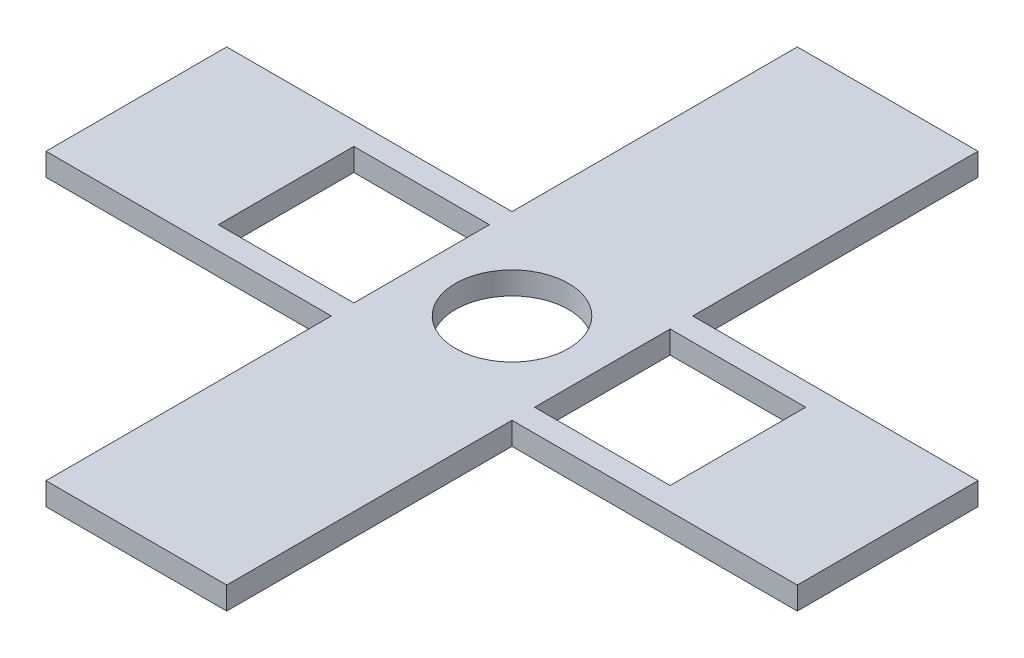
SolidWorks part; units mm, degrees
ref_plane "Front Plane" through (0, 0, 0) normal (0, 0, 1) x (1, 0, 0)
ref_plane "Top Plane" through (0, 0, 0) normal (0, 1, 0) x (1, 0, 0)
ref_plane "Right Plane" through (0, 0, 0) normal (1, 0, 0) x (0, 0, -1)
sketch "Sketch2" plane through (0, 0, 0) normal (0, 1, 0) x (1, 0, 0)
  line L0 (-21.1201, -5.08) -> (-5.08, -5.08)
  line L1 (-21.1201, 5.08) -> (-5.08, 5.08)
  line L2 (5.08, 3.81) -> (12.7, 3.81)
  line L3 (-12.7, 3.81) -> (-5.08, 3.81)
  line L4 (-12.7, 3.81) -> (-12.7, -3.81)
  line L5 (-12.7, -3.81) -> (-5.08, -3.81)
  line L6 (-5.08, 3.81) -> (-5.08, -3.81)
  line L7 (-12.7, 3.81) -> (-5.08, -3.81) construction
  line L8 (-12.7, -3.81) -> (-5.08, 3.81) construction
  line L9 (5.08, 3.81) -> (5.08, -3.81)
  line L10 (5.08, -3.81) -> (12.7, -3.81)
  line L11 (12.7, 3.81) -> (12.7, -3.81)
  line L12 (5.08, 3.81) -> (12.7, -3.81) construction
  line L13 (5.08, -3.81) -> (12.7, 3.81) construction
  line L14 (-21.1201, 5.08) -> (-21.1201, -5.08)
  line L15 (21.1201, -5.08) -> (5.08, -5.08)
  line L16 (21.1201, 5.08) -> (21.1201, -5.08)
  line L17 (-21.1201, 5.08) -> (21.1201, -5.08) construction
  line L18 (-21.1201, -5.08) -> (21.1201, 5.08) construction
  line L19 (-5.08, 21.1201) -> (5.08, 21.1201)
  line L20 (-5.08, 21.1201) -> (-5.08, 5.08)
  line L21 (-5.08, -21.1201) -> (5.08, -21.1201)
  line L22 (5.08, 21.1201) -> (5.08, 5.08)
  line L23 (-5.08, 21.1201) -> (5.08, -21.1201) construction
  line L24 (-5.08, -21.1201) -> (5.08, 21.1201) construction
  line L25 (5.08, 5.08) -> (21.1201, 5.08)
  line L26 (-5.08, -5.08) -> (-5.08, -21.1201)
  line L27 (5.08, -5.08) -> (5.08, -21.1201)
  circle A0 centre (0, 0) radius 3.175
  point P0 (0, 0)
extrude "Boss-Extrude2" add sketch "Sketch2" along normal blind 1.27
